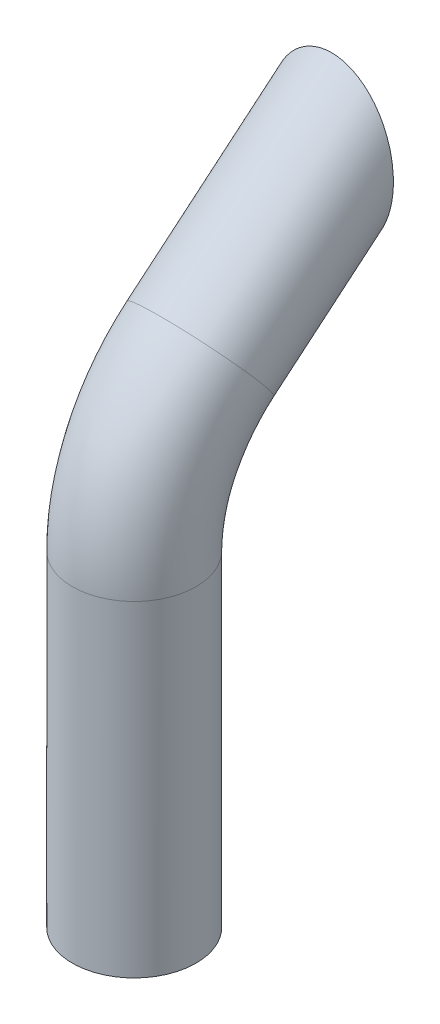
SolidWorks part; units mm, degrees
ref_plane "Front Plane" through (0, 0, 0) normal (0, 0, 1) x (1, 0, 0)
ref_plane "Top Plane" through (0, 0, 0) normal (0, 1, 0) x (1, 0, 0)
ref_plane "Right Plane" through (0, 0, 0) normal (1, 0, 0) x (0, 0, -1)
sketch "Sketch1" plane through (0, 0, 0) normal (1, 0, 0) x (0, 0, -1)
  line L0 (0, 0) -> (-82.7576, -69.4418)
  line L1 (-114.9067, -138.3858) -> (-114.9067, -296.4181)
  arc A0 (-82.7576, -69.4418) -> (-114.9067, -138.3858) centre (-24.9067, -138.3858) ccw
  point P6 (-114.9067, -96.4181)
  dimension "D4" = 90
  dimension "D1" = 150
  dimension "D2" = 200
  dimension "D3" = 130
ref_plane "Plane1" through (0, 0, 0) normal (0, -0.6428, 0.766) x (1, 0, 0)
sketch "Sketch2" plane through (0, 0, 0) normal (0, -0.6428, 0.766) x (1, 0, 0)
  circle A0 centre (0, 0) radius 30
  dimension "D1" = 60
sweep "Sweep-Thin1" add profiles "Sketch2" path "Sketch1" parameters "D1"=3
sketch "Sketch3" plane through (0, 0, 0) normal (1, 0, 0) x (0, 0, -1)
  line L1 (-19.2836, 22.9813) -> (59.5544, 22.9813)
  line L2 (-19.2836, 22.9813) -> (-19.2836, -72.6536)
  line L3 (-19.2836, -72.6536) -> (59.5544, -72.6536)
  line L4 (59.5544, 22.9813) -> (59.5544, -72.6536)
extrude "Cut-Extrude1" cut sketch "Sketch3" against normal mid plane 150
